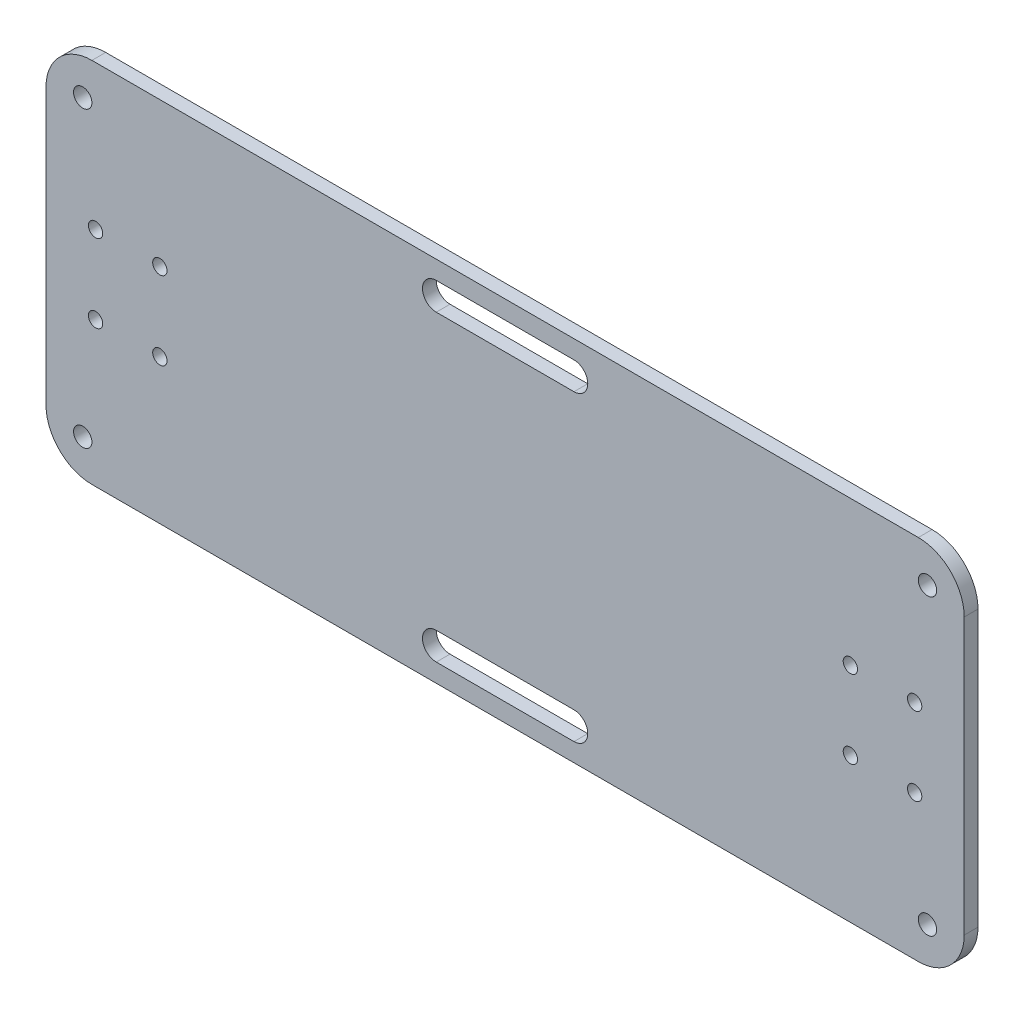
SolidWorks part; units mm, degrees
ref_plane "Front Plane" through (0, 0, 0) normal (0, 0, 1) x (1, 0, 0)
ref_plane "Top Plane" through (0, 0, 0) normal (0, 1, 0) x (1, 0, 0)
ref_plane "Right Plane" through (0, 0, 0) normal (1, 0, 0) x (0, 0, -1)
sketch "Sketch1" plane through (0, 0, 0) normal (0, 0, 1) x (1, 0, 0)
  line L1 (-100, 40) -> (100, 40)
  line L2 (-100, 40) -> (-100, -40)
  line L3 (-100, -40) -> (100, -40)
  line L4 (100, 40) -> (100, -40)
  line L5 (-100, 40) -> (100, -40) construction
  line L6 (-100, -40) -> (100, 40) construction
  point P0 (0, 0)
  dimension "D1" = 80
  dimension "D2" = 200
extrude "Boss-Extrude1" add sketch "Sketch1" along normal blind 3
sketch "Sketch2" plane through (0, 0, 3) normal (0, 0, 1) x (1, 0, 0)
  line L0 (-100, 40) -> (-100, -40) construction
  line L1 (100, 40) -> (-100, 40) construction
  line L2 (0, 40) -> (0, -40) construction
  line L3 (-100, -40) -> (100, -40) construction
  line L4 (-100, 0) -> (100, 0) construction
  line L5 (100, -40) -> (100, 40) construction
  circle A0 centre (-92, 32) radius 2
  circle A1 centre (-92, -32) radius 2
  circle A2 centre (92, -32) radius 2
  circle A3 centre (92, 32) radius 2
  dimension "D1" = 4
  dimension "D2" = 8
  dimension "D3" = 8
extrude "Cut-Extrude1" cut sketch "Sketch2" against normal through all
fillet "Fillet1" radius 10 4 edges at (-100, -40, 1.5) (100, -40, 1.5) (100, 40, 1.5) (-100, 40, 1.5)
sketch "Sketch3" plane through (0, 0, 0) normal (0, 0, -1) x (-1, 0, 0)
  circle A0 centre (89.2, -8.5) radius 1.5606
  circle A1 centre (75.2, -8.5) radius 1.5606
  circle A2 centre (75.2, 8.5) radius 1.5606
  circle A3 centre (89.2, 8.5) radius 1.5606
  circle A4 centre (-89.2, -8.5) radius 1.5606
  circle A5 centre (-75.2, -8.5) radius 1.5606
  circle A6 centre (-89.2, 8.5) radius 1.5606
  circle A7 centre (-75.2, 8.5) radius 1.5606
extrude "Cut-Extrude2" cut sketch "Sketch3" against normal through all
sketch "Sketch4" plane through (0, 0, 3) normal (0, 0, 1) x (1, 0, 0)
  line L0 (15, 33) -> (-15, 33) construction
  line L1 (15, 30) -> (-15, 30)
  line L2 (15, 36) -> (-15, 36)
  line L3 (90, 40) -> (-90, 40) construction
  line L4 (100, 0) -> (-100, 0) construction
  line L5 (100, -30) -> (100, 30) construction
  line L6 (-100, 30) -> (-100, -30) construction
  line L7 (15, -33) -> (-15, -33) construction
  line L8 (15, -30) -> (-15, -30)
  line L9 (15, -36) -> (-15, -36)
  arc A0 (15, 30) -> (15, 36) centre (15, 33) ccw
  arc A1 (-15, 36) -> (-15, 30) centre (-15, 33) ccw
  arc A2 (15, -30) -> (15, -36) centre (15, -33) cw
  arc A3 (-15, -36) -> (-15, -30) centre (-15, -33) cw
  point P2 (0, 33)
  point P9 (0, 40)
  point P18 (0, -33)
  dimension "D1" = 3
  dimension "D2" = 7
  dimension "D3" = 30
extrude "Cut-Extrude3" cut sketch "Sketch4" against normal through all
